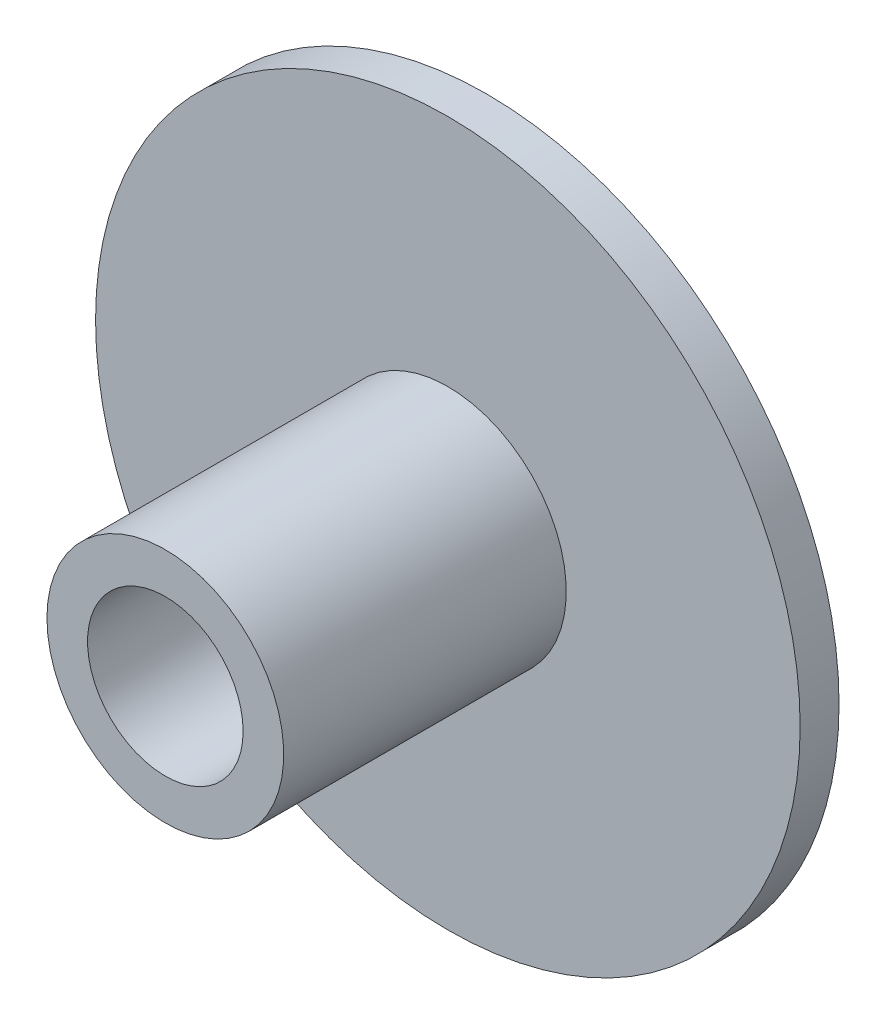
SolidWorks part; units mm, degrees
ref_plane "Front Plane" through (0, 0, 0) normal (0, 0, 1) x (1, 0, 0)
ref_plane "Top Plane" through (0, 0, 0) normal (0, 1, 0) x (1, 0, 0)
ref_plane "Right Plane" through (0, 0, 0) normal (1, 0, 0) x (0, 0, -1)
sketch "Sketch1" plane through (0, 0, 0) normal (0, 0, 1) x (1, 0, 0)
  circle A0 centre (0, 0) radius 7.8232
  dimension "D1" = 15.6464
extrude "Boss-Extrude1" add sketch "Sketch1" along normal blind 0.8636
sketch "Sketch2" plane through (0, 0, 0.8636) normal (0, 0, 1) x (1, 0, 0)
  circle A0 centre (0, 0) radius 2.6289
  dimension "D1" = 5.2578
extrude "Boss-Extrude2" add sketch "Sketch2" along normal blind 6.2738
hole_wizard "Tap Drill for #8-32 Tap1" positions "Sketch4" profile "Sketch3" hole size "#8-32" standard "ANSI Inch" end condition through all
sketch "Sketch4" plane through (0, 0, 7.1374) normal (0, 0, 1) x (1, 0, 0)
  point P0 (0, 0)
sketch "Sketch3" plane through (0, 0, 7.1374) normal (1, 0, 0) x (0, -1, 0)
  line L0 (0, 0) -> (0, 7.1374)
  line L1 (0, 7.1374) -> (1.7272, 7.1374)
  line L2 (1.7272, 7.1374) -> (1.7272, 0)
  line L5 (1.7272, 0) -> (0, 0)
  line L11 (0, -6.35) -> (0, 107.95) construction
  dimension "Thru Hole Dia." = 3.4544
  dimension "Thru Hole Depth" = 7.1374
